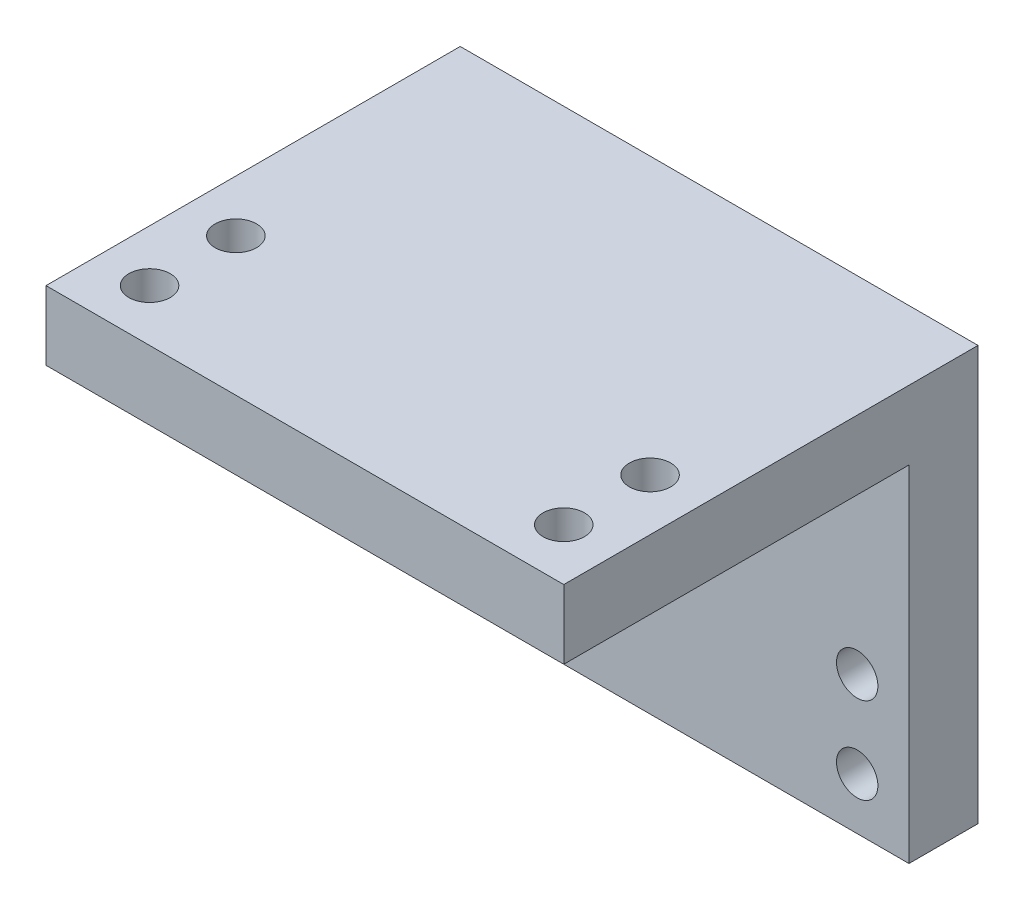
SolidWorks part; units mm, degrees
ref_plane "Front Plane" through (0, 0, 0) normal (0, 0, 1) x (1, 0, 0)
ref_plane "Top Plane" through (0, 0, 0) normal (0, 1, 0) x (1, 0, 0)
ref_plane "Right Plane" through (0, 0, 0) normal (1, 0, 0) x (0, 0, -1)
sketch "Sketch1" plane through (0, 0, 0) normal (1, 0, 0) x (0, 0, -1)
  line L0 (-2.1809, -16.8957) -> (28.2991, -16.8957)
  line L1 (28.2991, -16.8957) -> (28.2991, -47.3757)
  line L2 (28.2991, -47.3757) -> (23.2191, -47.3757)
  line L3 (23.2191, -47.3757) -> (23.2191, -21.9757)
  line L4 (23.2191, -21.9757) -> (-2.1809, -21.9757)
  line L5 (-2.1809, -21.9757) -> (-2.1809, -16.8957)
  dimension "D1" = 25.4
  dimension "D2" = 5.08
  dimension "D3" = 5.08
  dimension "D4" = 25.4
extrude "Boss-Extrude1" add sketch "Sketch1" along normal blind 38.1
sketch "Sketch2" plane through (0, 0, -28.2991) normal (0, 0, -1) x (-1, 0, 0)
  line L0 (-38.1, -47.3757) -> (-38.1, -16.8957) construction
  line L1 (-38.1, -47.3757) -> (0, -47.3757) construction
  circle A0 centre (-34.29, -43.5657) radius 1.524
  circle A1 centre (-3.81, -43.5657) radius 1.524
  circle A2 centre (-3.81, -37.2157) radius 1.524
  circle A3 centre (-34.29, -37.2157) radius 1.524
  dimension "D1" = 3.048
  dimension "D2" = 3.048
  dimension "D3" = 30.48
  dimension "D4" = 3.81
  dimension "D5" = 3.81
  dimension "D7" = 6.35
  dimension "D6" = 2
extrude "Cut-Extrude1" cut sketch "Sketch2" against normal through all
sketch "Sketch3" plane through (0, -16.8957, 0) normal (0, 1, 0) x (1, 0, 0)
  line L0 (0, 28.2991) -> (0, -2.1809) construction
  line L1 (38.1, -2.1809) -> (0, -2.1809) construction
  circle A0 centre (3.81, 1.6291) radius 1.524
  circle A1 centre (34.29, 1.6291) radius 1.524
  circle A2 centre (3.81, 7.9791) radius 1.524
  circle A3 centre (34.29, 7.9791) radius 1.524
  dimension "D1" = 3.048
  dimension "D2" = 3.048
  dimension "D7" = 6.35
  dimension "D3" = 30.48
  dimension "D4" = 3.81
  dimension "D5" = 3.81
  dimension "D6" = 2
extrude "Cut-Extrude2" cut sketch "Sketch3" against normal through all
